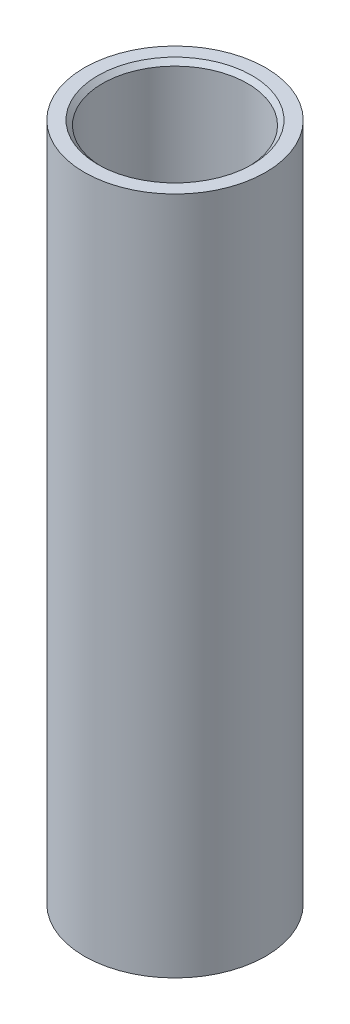
SolidWorks part; units mm, degrees
ref_plane "Front Plane" through (0, 0, 0) normal (0, 0, 1) x (1, 0, 0)
ref_plane "Top Plane" through (0, 0, 0) normal (0, 1, 0) x (1, 0, 0)
ref_plane "Right Plane" through (0, 0, 0) normal (1, 0, 0) x (0, 0, -1)
sketch "Sketch1" plane through (0, 0, 0) normal (0, 1, 0) x (1, 0, 0)
  circle A0 centre (0, 0) radius 3.175
  circle A1 centre (0, 0) radius 3.9688
  dimension "D1" = 6.35
extrude "Boss-Extrude1" add sketch "Sketch1" along normal blind 29.718
chamfer "Chamfer1" distance 0.2 angle 45 2 edges at (0, 0, 3.175) (0, 29.718, 3.175)
